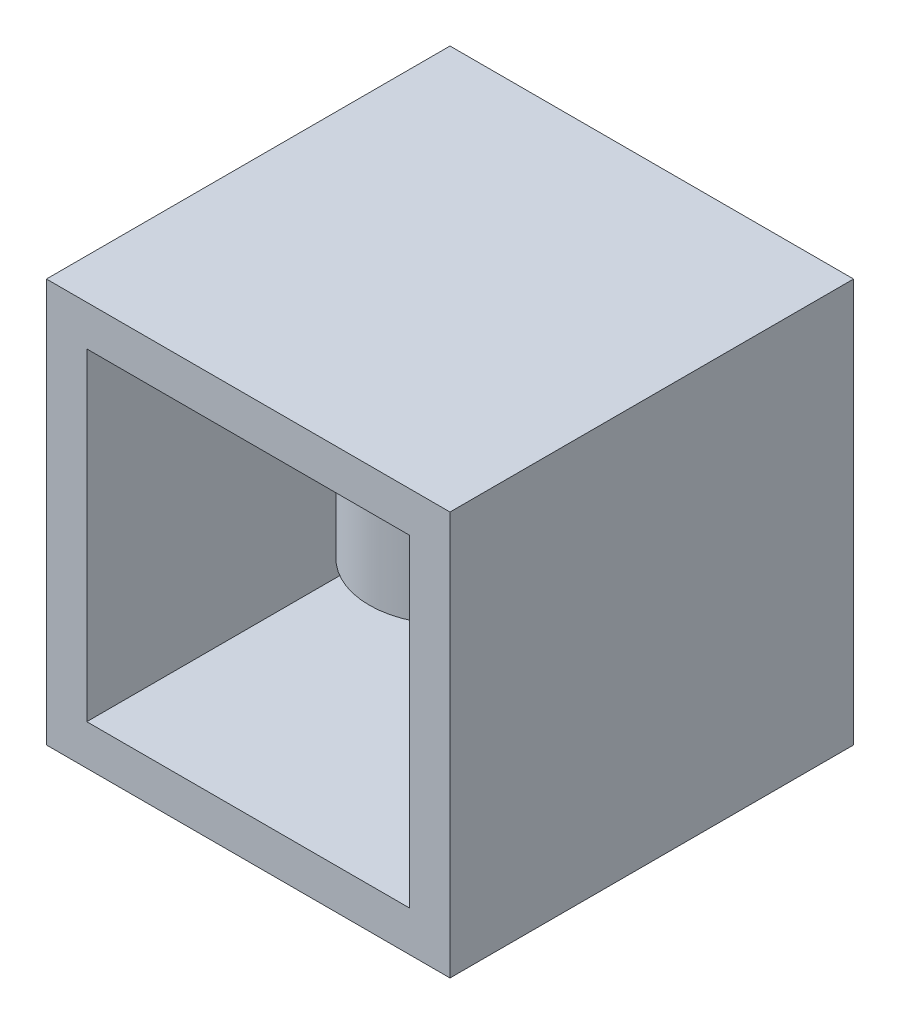
SolidWorks part; units mm, degrees
ref_plane "Front Plane" through (0, 0, 0) normal (0, 0, 1) x (1, 0, 0)
ref_plane "Top Plane" through (0, 0, 0) normal (0, 1, 0) x (1, 0, 0)
ref_plane "Right Plane" through (0, 0, 0) normal (1, 0, 0) x (0, 0, -1)
sketch "Sketch1" plane through (0, 0, 0) normal (0, 0, 1) x (1, 0, 0)
  line L1 (0, 0) -> (1000, 0)
  line L2 (0, 0) -> (0, 1000)
  line L3 (0, 1000) -> (1000, 1000)
  line L4 (1000, 0) -> (1000, 1000)
  line L5 (100, 900) -> (900, 900)
  line L6 (100, 900) -> (100, 100)
  line L7 (100, 100) -> (900, 100)
  line L8 (900, 900) -> (900, 100)
  dimension "D1" = 1000
  dimension "D2" = 1000
  dimension "D3" = 100
  dimension "D4" = 100
  dimension "D5" = 100
  dimension "D6" = 100
extrude "Boss-Extrude1" add sketch "Sketch1" along normal blind 1000 contours L1 L4 L3 L2 L5 L8 L7 L6
sketch "Sketch2" plane through (0, 900, 0) normal (0, -1, 0) x (1, 0, 0)
  line L0 (0, 1000) -> (0, 0) construction
  line L1 (0, 1000) -> (1000, 1000) construction
  circle A0 centre (500, 500) radius 200
  dimension "D1" = 400
  dimension "D2" = 500
  dimension "D3" = 500
extrude "Boss-Extrude2" add sketch "Sketch2" along normal blind 500
